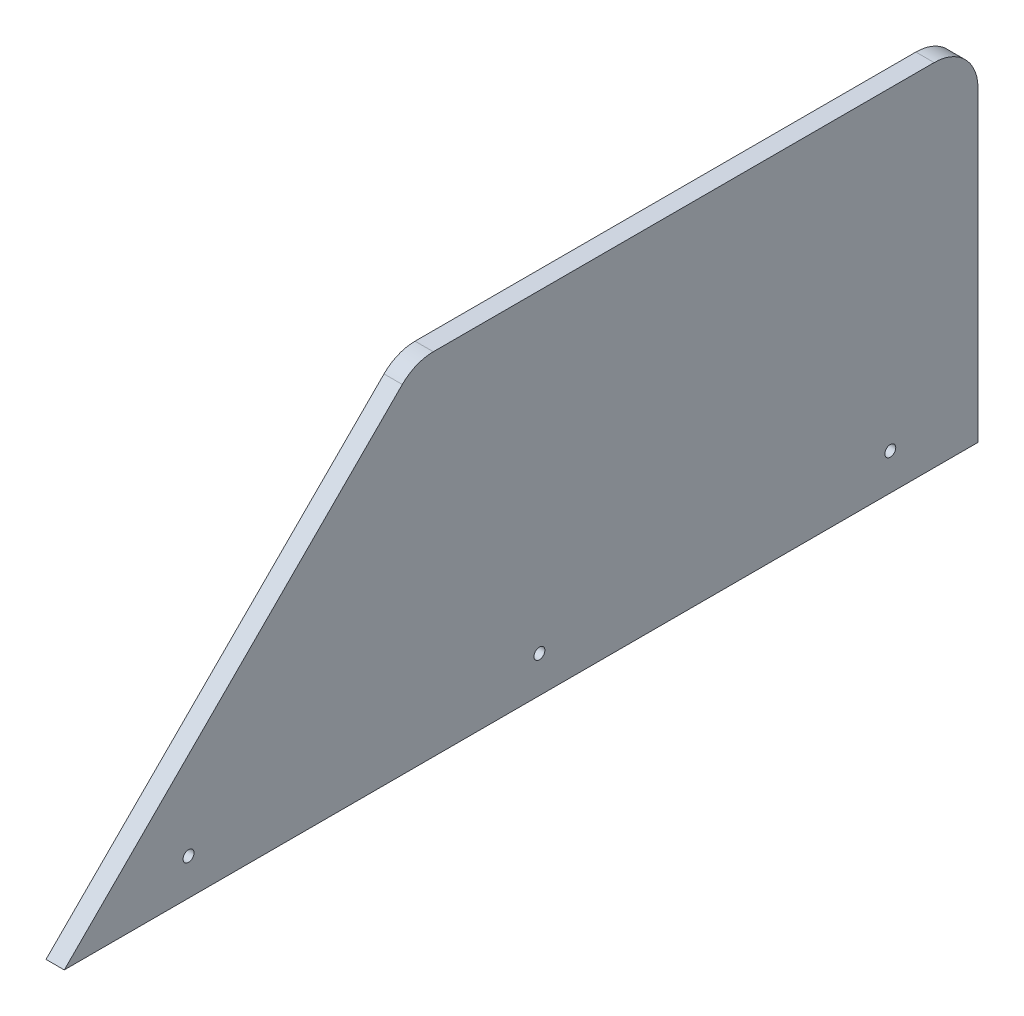
SolidWorks part; units mm, degrees
ref_plane "Front Plane" through (0, 0, 0) normal (0, 0, 1) x (1, 0, 0)
ref_plane "Top Plane" through (0, 0, 0) normal (0, 1, 0) x (1, 0, 0)
ref_plane "Right Plane" through (0, 0, 0) normal (1, 0, 0) x (0, 0, -1)
sketch "Sketch1" plane through (0, 0, 0) normal (1, 0, 0) x (0, 0, -1)
  line L0 (0, 0) -> (0, 96)
  line L1 (0, 96) -> (-154, 96)
  line L2 (-154, 96) -> (-250, 0)
  line L3 (-250, 0) -> (0, 0)
  line L4 (0, 10) -> (-240, 10) construction
  circle A0 centre (-120, 10) radius 1.5
  circle A1 centre (-24, 10) radius 1.5
  circle A2 centre (-216, 10) radius 1.5
  dimension "D5" = 3
  dimension "D6" = 96
  dimension "D1" = 250
  dimension "D2" = 96
  dimension "D3" = 45
  dimension "D4" = 10
  dimension "D7" = 96
extrude "Boss-Extrude1" add sketch "Sketch1" along normal blind 5
fillet "Fillet1" radius 12 2 edges at (2.5, 96, 0) (2.5, 96, 154)
